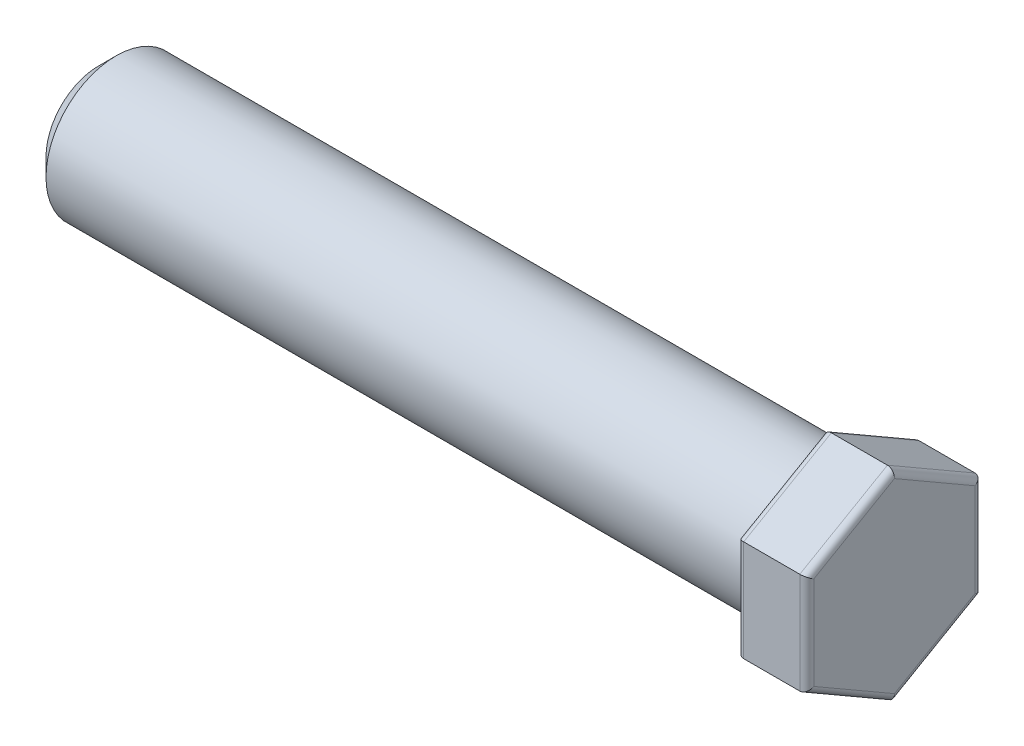
SolidWorks part; units mm, degrees
material "Cast Stainless Steel"
ref_plane "Front Plane" through (0, 0, 0) normal (0, 0, 1) x (1, 0, 0)
ref_plane "Top Plane" through (0, 0, 0) normal (0, 1, 0) x (1, 0, 0)
ref_plane "Right Plane" through (0, 0, 0) normal (1, 0, 0) x (0, 0, -1)
sketch "Sketch1" plane through (0, 0, 0) normal (1, 0, 0) x (0, 0, -1)
  line L1 (0, 2.8868) -> (-2.5, 1.4434)
  line L2 (-2.5, 1.4434) -> (-2.5, -1.4434)
  line L3 (-2.5, -1.4434) -> (0, -2.8868)
  line L4 (0, -2.8868) -> (2.5, -1.4434)
  line L5 (2.5, -1.4434) -> (2.5, 1.4434)
  line L6 (2.5, 1.4434) -> (0, 2.8868)
  circle A0 centre (0, 0) radius 2.5 construction
  dimension "D1" = 5
  dimension "D2" = 2.5
extrude "Boss-Extrude1" add sketch "Sketch1" along normal mid plane 2
fillet "Fillet1" radius 0.2 12 edges at (-1, 2.1651, 1.25) (-1, 0, 2.5) (-1, -2.1651, 1.25) (-1, -2.1651, -1.25) (-1, 0, -2.5) (-1, 2.1651, -1.25) (1, 0, -2.5) (1, -2.1651, -1.25) (1, -2.1651, 1.25) (1, 0, 2.5) (1, 2.1651, 1.25) (1, 2.1651, -1.25)
sketch "Sketch2" plane through (-1, 0, 0) normal (-1, 0, 0) x (0, 0, 1)
  circle A0 centre (0, 0) radius 2
  dimension "D1" = 4
extrude "Boss-Extrude2" add sketch "Sketch2" along normal blind 20.7
chamfer "Chamfer1" distance 0.5 angle 45 1 edges at (-21.7, 0, 2)
fillet "Fillet2" radius 0.2 1 edges at (-1, 0, -2)
